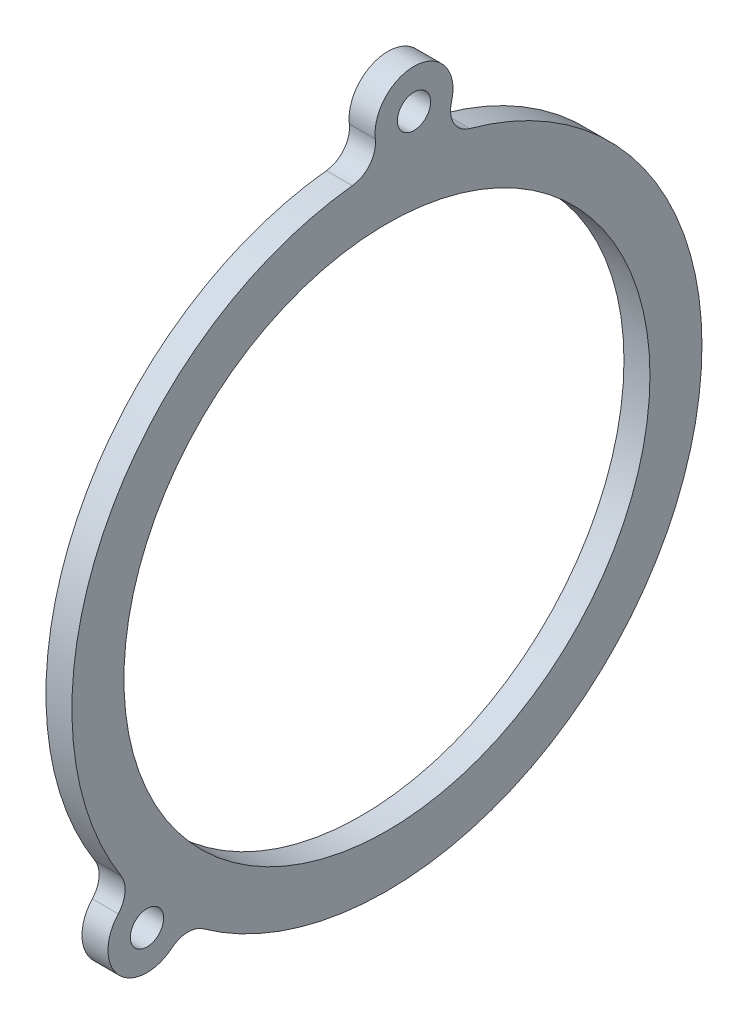
SolidWorks part; units mm, degrees
ref_plane "Front Plane" through (0, 0, 0) normal (0, 0, 1) x (1, 0, 0)
ref_plane "Top Plane" through (0, 0, 0) normal (0, 1, 0) x (1, 0, 0)
ref_plane "Right Plane" through (0, 0, 0) normal (1, 0, 0) x (0, 0, -1)
sketch "Sketch1" plane through (0, 0, 0) normal (1, 0, 0) x (0, 0, -1)
  circle A0 centre (0, 0) radius 32.131
  arc A1 (0.5393, 38.4772) -> (-30.7316, -23.1594) centre (0, 0) ccw
  arc A2 (5.4385, 38.0948) -> (0.5393, 38.4772) centre (3.3064, 42.3534) ccw
  arc A3 (-30.7316, -23.1594) -> (-24.8557, -29.3766) centre (-29.3158, -27.7065) ccw
  arc A4 (-24.8557, -29.3766) -> (5.4385, 38.0948) centre (0, 0) ccw
  circle A5 centre (3.3064, 42.3534) radius 2.032
  circle A6 centre (-29.3158, -27.7065) radius 2.032
  circle A7 centre (3.3064, 42.3534) radius 2.032 construction
  circle A8 centre (-29.3158, -27.7065) radius 2.032 construction
  dimension "D1" = 64.262
  dimension "D2" = 6.35
  dimension "D3" = 4.064
  dimension "D4" = 9.525
extrude "Boss-Extrude1" add sketch "Sketch1" along normal blind 3.175
fillet "Fillet1" radius 3.175 4 edges at (1.5875, -29.3766, 24.8557) (1.5875, -23.1594, 30.7316) (1.5875, 38.0948, -5.4385) (1.5875, 38.4772, -0.5393)
